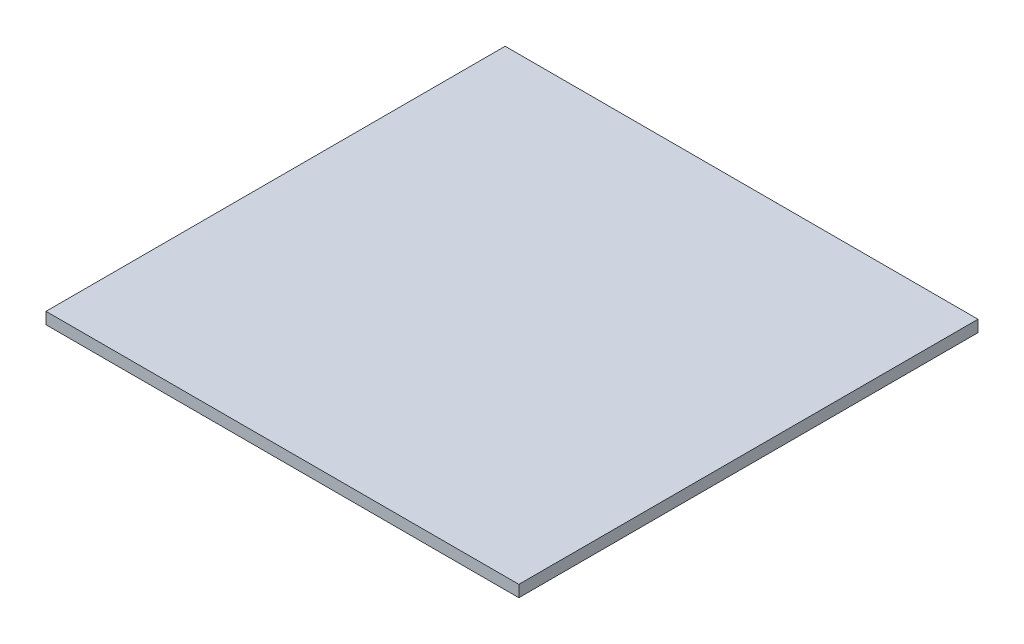
SolidWorks part; units mm, degrees
ref_plane "Alzado" through (0, 0, 0) normal (0, 0, 1) x (1, 0, 0)
ref_plane "Planta" through (0, 0, 0) normal (0, 1, 0) x (1, 0, 0)
ref_plane "Vista lateral" through (0, 0, 0) normal (1, 0, 0) x (0, 0, -1)
sketch "Croquis2" plane through (0, 0, 0) normal (0, 1, 0) x (1, 0, 0)
  line L1 (0, 0) -> (69, 0)
  line L2 (0, 0) -> (0, 67)
  line L3 (0, 67) -> (69, 67)
  line L4 (69, 0) -> (69, 67)
  dimension "D1" = 69
  dimension "D2" = 67
extrude "Saliente-Extruir1" add sketch "Croquis2" along normal blind 1.7
